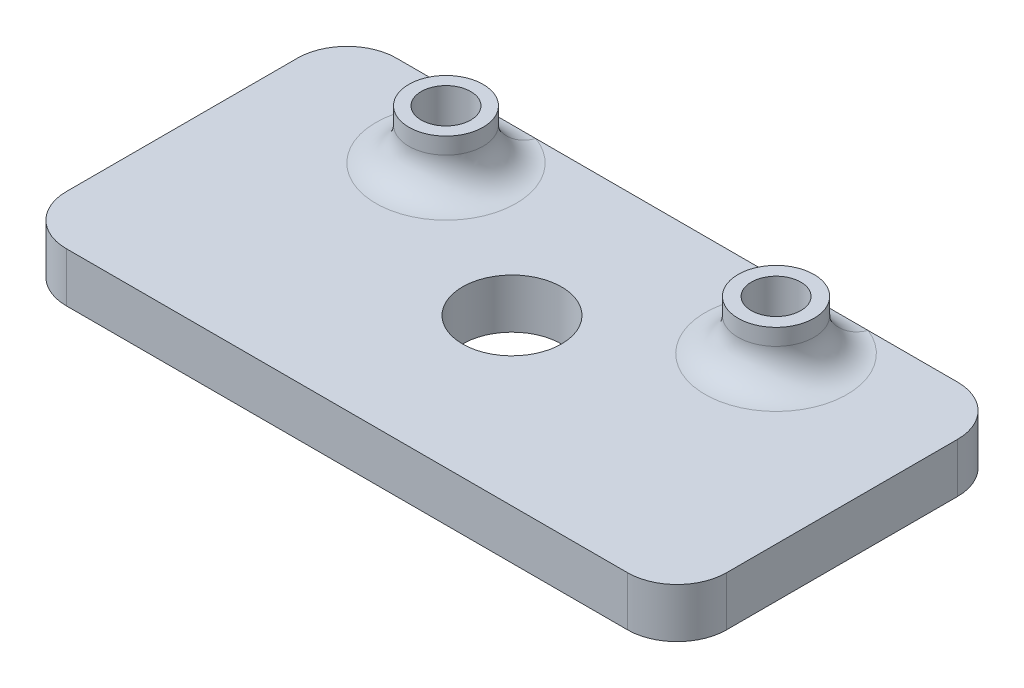
SolidWorks part; units mm, degrees
ref_plane "Front Plane" through (0, 0, 0) normal (0, 0, 1) x (1, 0, 0)
ref_plane "Top Plane" through (0, 0, 0) normal (0, 1, 0) x (1, 0, 0)
ref_plane "Right Plane" through (0, 0, 0) normal (1, 0, 0) x (0, 0, -1)
sketch "Sketch1" plane through (0, 0, 0) normal (0, 1, 0) x (1, 0, 0)
  line L0 (0, 10) -> (0, -10) construction
  line L1 (-20, 10) -> (20, 10)
  line L2 (-20, 10) -> (-20, -10)
  line L3 (-20, -10) -> (20, -10)
  line L4 (20, 10) -> (20, -10)
  line L5 (-20, 10) -> (20, -10) construction
  line L6 (-20, -10) -> (20, 10) construction
  line L7 (-20, 6) -> (20, 6) construction
  circle A0 centre (-10, 6) radius 1.5
  circle A1 centre (10, 6) radius 1.5
  point P0 (0, 0)
  dimension "D4" = 3
  dimension "D1" = 40
  dimension "D2" = 20
  dimension "D3" = 4
  dimension "D5" = 10
extrude "Boss-Extrude1" add sketch "Sketch1" along normal blind 3
fillet "Fillet1" radius 3 4 edges at (-20, 1.5, -10) (20, 1.5, -10) (20, 1.5, 10) (-20, 1.5, 10)
sketch "Sketch2" plane through (0, 3, 0) normal (0, 1, 0) x (1, 0, 0)
  circle A0 centre (-10, 6) radius 2.25
  circle A1 centre (10, 6) radius 2.3
  circle A2 centre (10, 6) radius 1.5 construction
  circle A3 centre (-10, 6) radius 1.5 construction
  circle A4 centre (10, 6) radius 1.5
  circle A5 centre (-10, 6) radius 1.5
  dimension "D1" = 4.5
  dimension "D2" = 4.6
extrude "Boss-Extrude2" add sketch "Sketch2" along normal blind 3
sketch "Sketch3" plane through (0, 3, 0) normal (0, 1, 0) x (1, 0, 0)
  circle A0 centre (0, 0) radius 3
  dimension "D1" = 6
extrude "Cut-Extrude1" cut sketch "Sketch3" against normal blind 10
fillet "Fillet2" radius 2 2 edges at (10, 3, -3.7) (-10, 3, -3.75)
